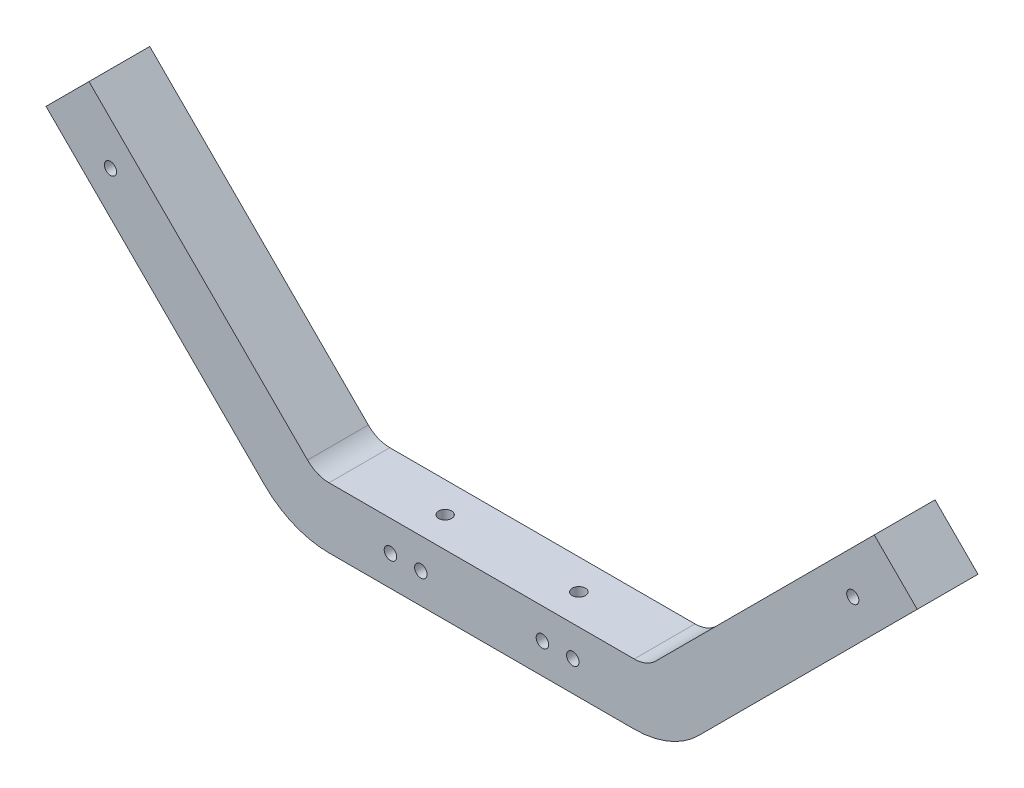
SolidWorks part; units mm, degrees
ref_plane "前视基准面" through (0, 0, 0) normal (0, 0, 1) x (1, 0, 0)
ref_plane "上视基准面" through (0, 0, 0) normal (0, 1, 0) x (1, 0, 0)
ref_plane "右视基准面" through (0, 0, 0) normal (1, 0, 0) x (0, 0, -1)
sketch "草图1" plane through (0, 0, 0) normal (0, 0, 1) x (1, 0, 0)
  line L0 (-143.3553, 70.7107) -> (-129.2132, 84.8528)
  line L1 (-129.2132, 84.8528) -> (-54.3604, 10)
  line L2 (-54.3604, 10) -> (54.3604, 10)
  line L3 (54.3604, 10) -> (129.2132, 84.8528)
  line L4 (129.2132, 84.8528) -> (143.3553, 70.7107)
  line L5 (143.3553, 70.7107) -> (62.6447, -10)
  line L6 (62.6447, -10) -> (-62.6447, -10)
  line L7 (-62.6447, -10) -> (-143.3553, 70.7107)
  line L8 (-136.2843, 77.7817) -> (-58.5025, 0) construction
  line L9 (-58.5025, 0) -> (58.5025, 0) construction
  line L10 (58.5025, 0) -> (136.2843, 77.7817) construction
  line L11 (-115.0711, 42.4264) -> (-100.9289, 56.5685) construction
  line L12 (100.9289, 56.5685) -> (115.0711, 42.4264) construction
  line L13 (-108, 49.4975) -> (108, 49.4975) construction
  circle A0 centre (-122.1421, 63.6396) radius 2
  circle A1 centre (122.1421, 63.6396) radius 2
  point P17 (0, 0)
  dimension "D4" = 4
  dimension "D5" = 4
  dimension "D1" = 20
  dimension "D2" = 20
  dimension "D3" = 20
  dimension "D6" = 135
  dimension "D7" = 135
  dimension "D8" = 20
  dimension "D9" = 20
  dimension "D10" = 40
  dimension "D11" = 40
  dimension "D12" = 90
  dimension "D13" = 216
  dimension "D14" = 10
extrude "凸台-拉伸1" add sketch "草图1" along normal blind 20
fillet "圆角1" radius 10 2 edges at (54.3604, 10, 10) (-54.3604, 10, 10)
fillet "圆角2" radius 30 2 edges at (62.6447, -10, 10) (-62.6447, -10, 10)
sketch "草图2" plane through (0, 0, 20) normal (0, 0, 1) x (1, 0, 0)
  line L0 (50.2183, 10) -> (-50.2183, 10) construction
  circle A0 centre (-30, 0) radius 2.05
  circle A1 centre (30, 0) radius 2.05
  dimension "D1" = 4.1
  dimension "D2" = 4.1
  dimension "D3" = 60
  dimension "D4" = 30
  dimension "D5" = 10
  dimension "D6" = 10
extrude "切除-拉伸1" cut sketch "草图2" against normal blind 50
sketch "草图3" plane through (0, 0, 0) normal (0, 0, -1) x (-1, 0, 0)
  circle A0 centre (-30, 0) radius 5
  circle A1 centre (30, 0) radius 5
  dimension "D1" = 10
  dimension "D2" = 10
extrude "切除-拉伸2" cut sketch "草图3" against normal blind 5
sketch "草图4" plane through (0, 0, 0) normal (0, 0, -1) x (-1, 0, 0)
  line L0 (-50.2183, 10) -> (50.2183, 10) construction
  circle A0 centre (-20, 0) radius 2.05
  circle A1 centre (20, 0) radius 2.05
  dimension "D1" = 4.1
  dimension "D2" = 4.1
  dimension "D3" = 40
  dimension "D4" = 20
  dimension "D5" = 10
  dimension "D6" = 10
extrude "切除-拉伸3" cut sketch "草图4" against normal blind 29
sketch "草图5" plane through (0, -10, 0) normal (0, -1, 0) x (1, 0, 0)
  line L0 (-50.2183, 20) -> (50.2183, 20) construction
  circle A0 centre (-22, 10) radius 2.15
  circle A1 centre (22, 10) radius 2.15
  dimension "D1" = 4.3
  dimension "D2" = 4.3
  dimension "D3" = 44
  dimension "D4" = 22
  dimension "D5" = 10
  dimension "D6" = 10
extrude "切除-拉伸4" cut sketch "草图5" against normal blind 29
